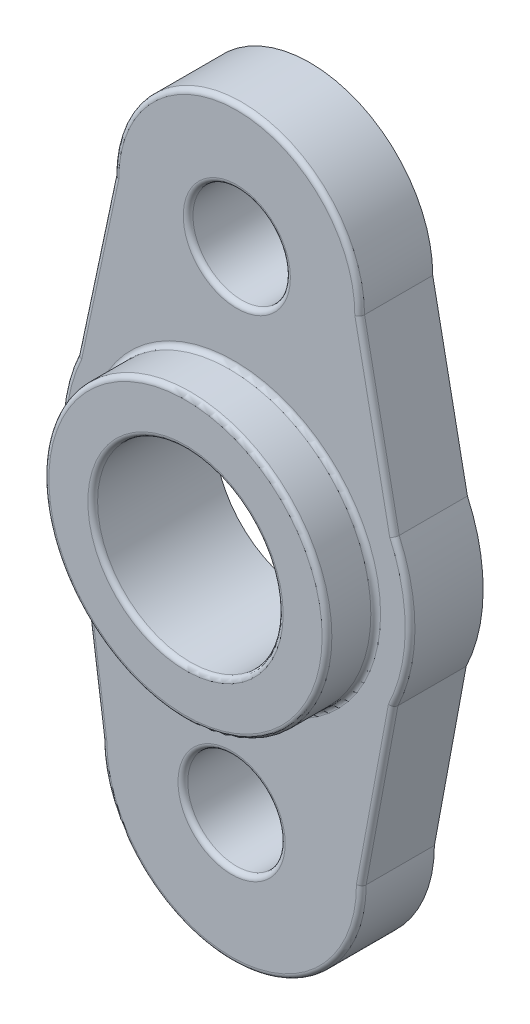
SolidWorks part; units mm, degrees
ref_plane "Front Plane" through (0, 0, 0) normal (0, 0, 1) x (1, 0, 0)
ref_plane "Top Plane" through (0, 0, 0) normal (0, 1, 0) x (1, 0, 0)
ref_plane "Right Plane" through (0, 0, 0) normal (1, 0, 0) x (0, 0, -1)
sketch "Sketch1" plane through (0, 0, 0) normal (0, 0, 1) x (1, 0, 0)
  line L1 (-24.1558, 101.187) -> (-31.7346, 65.5436)
  line L2 (26.2965, 101.187) -> (33.4152, 65.5159)
  line L3 (-26.6333, 0) -> (-31.4814, 35.1085)
  line L4 (26.6333, 0) -> (33.154, 35.1085)
  circle A0 centre (1.0704, 101.187) radius 10
  circle A1 centre (0, 0) radius 10
  circle A2 centre (0.5352, 50.5935) radius 19.05
  arc A3 (-26.6333, 0) -> (26.6333, 0) centre (0, 0) ccw
  arc A6 (33.154, 35.1085) -> (33.4152, 65.5159) centre (0.5352, 50.5935) ccw
  arc A8 (-31.7346, 65.5436) -> (-31.4814, 35.1085) centre (0.5352, 50.5935) ccw
  arc A9 (26.2965, 101.187) -> (-24.1558, 101.187) centre (1.0704, 101.187) ccw
  point P7 (0, 0)
  point P8 (0, 0)
  point P9 (0, 0)
  point P18 (-31.7405, 65.5159)
  point P19 (33.154, 65.5159)
  point P20 (-31.7346, 35.1085)
extrude "Boss-Extrude1" add sketch "Sketch1" along normal blind 15
sketch "Sketch2" plane through (0, 0, 15) normal (0, 0, 1) x (1, 0, 0)
  circle A0 centre (0.5352, 50.5935) radius 19.05
  circle A1 centre (0.5352, 50.5935) radius 29.05
  dimension "D1" = 10
extrude "Boss-Extrude2" add sketch "Sketch2" along normal blind 10
fillet "Fillet2" radius 1 11 edges at (29.5852, 50.5935, 15) (10, 0, 15) (29.8559, 83.3514, 15) (36.6417, 50.2834, 15) (29.8936, 17.5542, 15) (0, -26.6333, 15) (-29.0573, 17.5542, 15) (-35.0283, 50.2976, 15) (-27.9452, 83.3653, 15) (1.0704, 126.4131, 15) (11.0704, 101.187, 15)
fillet "Fillet3" radius 1 2 edges at (19.5852, 50.5935, 25) (29.5852, 50.5935, 25)
